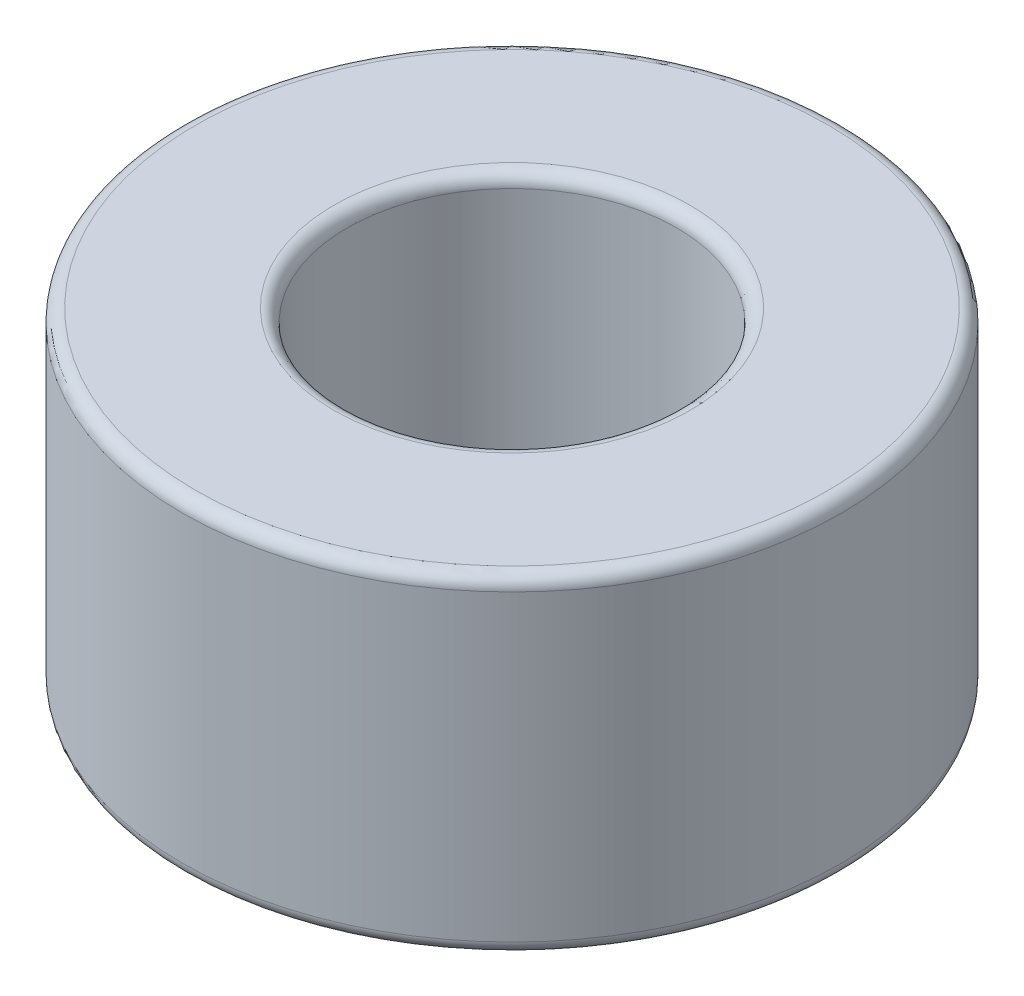
SolidWorks part; units mm, degrees
ref_plane "Front Plane" through (0, 0, 0) normal (0, 0, 1) x (1, 0, 0)
ref_plane "Top Plane" through (0, 0, 0) normal (0, 1, 0) x (1, 0, 0)
ref_plane "Right Plane" through (0, 0, 0) normal (1, 0, 0) x (0, 0, -1)
sketch "Sketch1" plane through (0, 0, 0) normal (0, 1, 0) x (1, 0, 0)
  circle A0 centre (0, 0) radius 3.175
  circle A1 centre (0, 0) radius 1.5875
  dimension "OD" = 6.35
  dimension "Hole Dia" = 3.175
extrude "Boss-Extrude1" add sketch "Sketch1" along normal mid plane 3.175
fillet "Fillet1" radius 0.127 4 edges at (0, -1.5875, 3.175) (0, 1.5875, 3.175) (0, -1.5875, 1.5875) (0, 1.5875, 1.5875)
equation "\"D1@Fillet1\"=\"Thickness@Boss-Extrude1\"/25"
